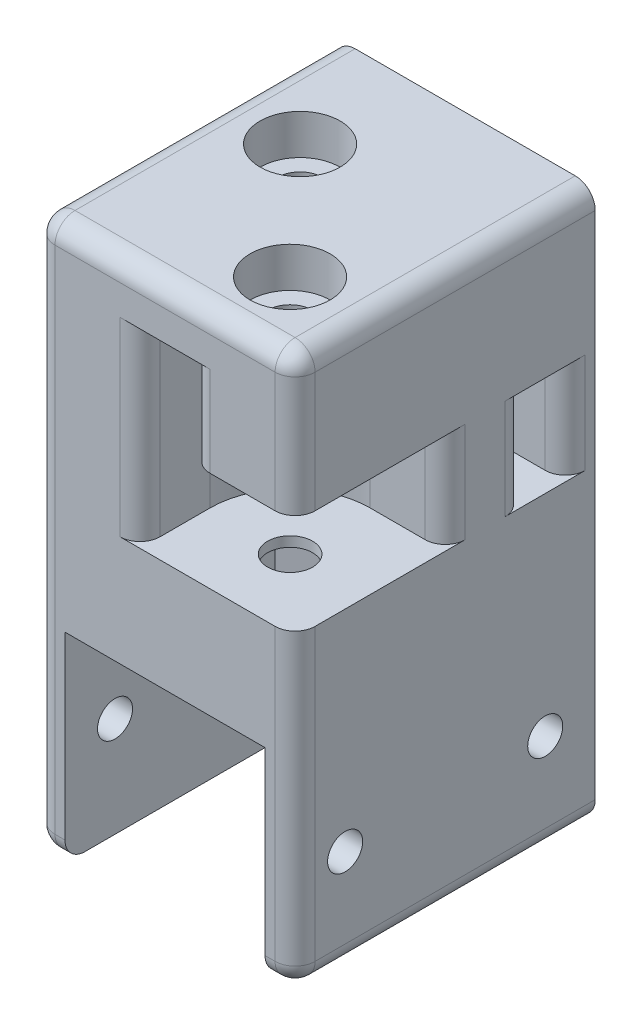
SolidWorks part; units mm, degrees
material "ABS"
ref_plane "Front Plane" through (0, 0, 0) normal (0, 0, 1) x (1, 0, 0)
ref_plane "Top Plane" through (0, 0, 0) normal (0, 1, 0) x (1, 0, 0)
ref_plane "Right Plane" through (0, 0, 0) normal (1, 0, 0) x (0, 0, -1)
sketch "Sketch2" plane through (0, 0, 0) normal (0, 1, 0) x (1, 0, 0)
  line L1 (-10, -15) -> (10, -15)
  line L2 (-10, -15) -> (-10, 15)
  line L3 (-10, 15) -> (10, 15)
  line L4 (10, -15) -> (10, 15)
  line L5 (-10, -15) -> (10, 15) construction
  line L6 (-10, 15) -> (10, -15) construction
  point P0 (0, 0)
  dimension "D1" = 20
  dimension "D2" = 30
extrude "Boss-Extrude1" add sketch "Sketch2" along normal blind 30
sketch "Sketch3" plane through (0, 30, 0) normal (0, 1, 0) x (1, 0, 0)
  line L0 (0, -15) -> (0, 15) construction
  line L1 (-10, -15) -> (10, -15) construction
  line L2 (10, 15) -> (-10, 15) construction
  line L3 (5.5, -1) -> (10, -1)
  line L4 (10, -15) -> (10, 15) construction
  line L6 (-5.5, 11) -> (-10, 11)
  line L7 (-10, 15) -> (-10, -15) construction
  line L8 (-10, 11) -> (-10, -1.3619)
  line L9 (-1.5, -8) -> (-1.5, -1.7446)
  line L10 (1.5, 4) -> (1.5, -2.2554)
  line L11 (-1.5, -8) -> (-1.5, -15)
  line L12 (1.5, -15) -> (1.5, -13.7446)
  line L13 (10, 11) -> (-5.5, 11)
  line L14 (10, 11) -> (10, 8)
  line L15 (10, 8) -> (0.2446, 8)
  line L17 (10, -15) -> (10, -1)
  line L18 (1.5, -15) -> (10, -15)
  line L19 (-5.5, -3) -> (-10, -3)
  line L20 (-10, -3) -> (-10, -1.3619)
  circle A0 centre (5.5, -8) radius 2.25
  circle A1 centre (-5.5, 4) radius 2.25
  arc A2 (5.5, -1) -> (1.5, -13.7446) centre (5.5, -8) ccw
  arc A3 (-5.5, 11) -> (-10, -1.3619) centre (-5.5, 4) cw
  line M1 (10, -15) -> (10, 15)
  line M3 (-10, 15) -> (-10, -15)
  line M4 (-10, -15) -> (10, -15)
  dimension "D3" = 4.5
  dimension "D4" = 4.5
  dimension "D7" = 7
  dimension "D8" = 7
  dimension "D1" = 5.5
  dimension "D2" = 7
  dimension "D5" = 12
  dimension "D6" = 5.5
  dimension "D9" = 3
extrude "Cut-Extrude2" cut sketch "Sketch3" against normal blind 19 contours L0 A2 L3 A0 M1 | A2 L0 | A3 L0 L6 A1 M3 | L0 A3 | L0 A2 L10 A3 | A2 L0 A3 L9 | L0 A2 L11 M4 | L0 L12 A2 M4 | L0 L15 L13 M1 | L15 L0 L13 A3 | L19 A3 M3
sketch "Sketch5" plane through (0, 30, 0) normal (0, 1, 0) x (1, 0, 0)
  line L1 (10, -15) -> (-10, -15)
  line L2 (10, -15) -> (10, 15)
  line L3 (10, 15) -> (-10, 15)
  line L4 (-10, -15) -> (-10, 15)
  line L5 (10, -15) -> (-10, 15) construction
  line L6 (10, 15) -> (-10, -15) construction
  point P0 (0, 0)
extrude "Boss-Extrude2" add sketch "Sketch5" along normal blind 5
sketch "Sketch6" plane through (0, 30, 0) normal (0, -1, 0) x (1, 0, 0)
  line L3 (-1.5, 15) -> (10, 15) construction
  line L8 (1.5, 2.2554) -> (1.5, 15)
  line L9 (-1.5, 15) -> (10, 15) construction
  line L10 (1.5, 15) -> (10, 15)
  line L11 (10, 15) -> (10, 1)
  line L12 (10, 1) -> (5.5, 1)
  line L13 (5.5, 1) -> (10, 1) construction
  circle A0 centre (5.5, 8) radius 2.2812
  arc A1 (5.5, 1) -> (1.5, 2.2554) centre (5.5, 8) cw
extrude "Boss-Extrude3" add sketch "Sketch6" along normal blind 9
sketch "Sketch7" plane through (0, 11, 0) normal (0, 1, 0) x (1, 0, 0)
  line L0 (0.2446, 8) -> (-10, 8)
  line L1 (-5.5, -3) -> (-10, -3)
  line L2 (-10, 11) -> (-10, -3) construction
  line L3 (-1.5, -15) -> (-1.5, -1.7446) construction
  line L4 (-1.5, -1.7446) -> (-1.5, -8)
  line L5 (1.5, -2.2554) -> (1.5, 4)
  line L6 (1.5, 4) -> (1.5, -2.2554) construction
  line L7 (-10, 8) -> (-10, -3)
  arc A0 (0.2446, 8) -> (1.5, 4) centre (-5.5, 4) cw
  arc A1 (-1.5, -1.7446) -> (-5.5, -3) centre (-5.5, 4) cw
  arc A2 (-5.5, -3) -> (-1.5, -1.7446) centre (-5.5, 4) ccw construction
  arc A3 (1.5, -2.2554) -> (-1.5, -8) centre (5.5, -8) ccw
  circle A4 centre (-5.5, 4) radius 2.25
  arc A5 (-5.5, -3) -> (-1.5, -1.7446) centre (-5.5, 4) ccw construction
extrude "Boss-Extrude4" add sketch "Sketch7" along normal blind 9
sketch "Sketch15" plane through (0, 30, 0) normal (0, -1, 0) x (1, 0, 0)
  line L0 (10, -11) -> (-10, -11) construction
  line L5 (10, -8) -> (10, -11)
  line L6 (10, -11) -> (-5.5, -11)
  line L7 (0.2446, -8) -> (10, -8)
  arc A0 (0.2446, -8) -> (-5.5, -11) centre (-5.5, -4) cw
extrude "Boss-Extrude6" add sketch "Sketch15" along normal blind 9
sketch "Sketch16" [suppressed] plane through (0, 11, 0) normal (0, 1, 0) x (1, 0, 0)
  line L0 (10, -15) -> (10, -1)
  line L1 (10, -1) -> (5.5, -1)
  line L2 (10, -15) -> (1.5, -15)
  line L3 (-1.5, -15) -> (10, -15) construction
  line L4 (1.5, -15) -> (1.5, -2.2554)
  circle A0 centre (5.5, -8) radius 2.25
  arc A1 (5.5, -1) -> (1.5, -2.2554) centre (5.5, -8) ccw construction
  arc A2 (1.5, -2.2554) -> (5.5, -1) centre (5.5, -8) cw
  dimension "D1" = 3
extrude "Boss-Extrude7" [suppressed] add sketch "Sketch16" along normal blind 9
sketch "Sketch17" [suppressed] plane through (0, 30, 0) normal (0, -1, 0) x (1, 0, 0)
  line L0 (0.2446, -8) -> (-10, -8)
  line L1 (-10, -11) -> (-10, 3) construction
  line L2 (-10, -8) -> (-10, 3)
  line L3 (1.5, -4) -> (1.5, 15) construction
  line L4 (1.5, -4) -> (1.5, 2.2554)
  line L5 (-1.5, 8.0934) -> (-1.5, 1.7446)
  line L6 (-1.5, 15) -> (-1.5, 1.7446) construction
  line L7 (-5.5, 3) -> (-10, 3)
  line L8 (-5.5, 3) -> (-10, 3) construction
  circle A0 centre (-5.5, -4) radius 2.25
  arc A1 (-1.5, 1.7446) -> (-5.5, 3) centre (-5.5, -4) ccw
  arc A2 (-1.5, 1.7446) -> (-5.5, 3) centre (-5.5, -4) ccw construction
  arc A3 (0.2446, -8) -> (1.5, -4) centre (-5.5, -4) ccw
  arc A4 (1.5, 2.2554) -> (-1.5, 8) centre (5.5, 8) cw
  arc A5 (-1.5, 1.7446) -> (-5.5, 3) centre (-5.5, -4) ccw construction
  circle M1 centre (-5.5, -4) radius 2.25
  line M2 (-10, 3) -> (-10, -11)
  arc M6 (-5.5, -11) -> (1.5, -4) centre (-5.5, -4) ccw
  line M7 (1.5, -4) -> (1.5, 15)
  arc M13 (-1.5, 1.7446) -> (-5.5, 3) centre (-5.5, -4) ccw
extrude "Boss-Extrude8" [suppressed] add sketch "Sketch17" along normal blind 9 contours A4 L5 L0 M7 M13 M2 M6 M1
sketch "Sketch18" [suppressed] plane through (0, 11, 0) normal (0, 1, 0) x (1, 0, 0)
  line L0 (10, 11) -> (10, 8)
  line L1 (10, 8) -> (0.2446, 8)
  line L2 (10, 11) -> (-10, 11) construction
  line L3 (10, 11) -> (-5.5, 11)
  arc A0 (0.2446, 8) -> (-5.5, 11) centre (-5.5, 4) ccw
extrude "Boss-Extrude9" [suppressed] add sketch "Sketch18" along normal blind 9
sketch "Sketch9" [suppressed] plane through (0, 0, -15) normal (0, 0, -1) x (-1, 0, 0)
  line L0 (-10, 0) -> (10, 0) construction
  line L1 (-5.5, 3) -> (5.5, 3)
  line L2 (-5.5, 3) -> (-5.5, 0)
  line L3 (-5.5, 0) -> (5.5, 0)
  line L4 (5.5, 3) -> (5.5, 0)
  line L5 (-5.5, 3) -> (5.5, 0) construction
  line L6 (-5.5, 0) -> (5.5, 3) construction
  line L9 (-10, 35) -> (-10, 0) construction
  point P0 (0, 1.5)
  dimension "D1" = 3
  dimension "D2" = 11
  dimension "D3" = 4.5
extrude "Boss-Extrude5" [suppressed] add sketch "Sketch9" along normal blind 7
sketch "Sketch10" [suppressed] plane through (0, 3, 0) normal (0, 1, 0) x (1, 0, 0)
  line L0 (-5.5, 15) -> (5.5, 15) construction
  circle A0 centre (0, 18.5) radius 1.75
  dimension "D1" = 3.5
  dimension "D2" = 3.5
extrude "Cut-Extrude4" [suppressed] cut sketch "Sketch10" against normal through all
sketch "Sketch11" [suppressed] plane through (0, 3, 0) normal (0, 1, 0) x (1, 0, 0)
  circle A0 centre (0, 18.5) radius 3
  dimension "D1" = 6
extrude "Cut-Extrude5" [suppressed] cut sketch "Sketch11" against normal blind 1
sketch "Sketch8" plane through (0, 35, 0) normal (0, 1, 0) x (1, 0, 0)
  line L0 (0, -15) -> (0, 15) construction
  line L1 (-10, -15) -> (10, -15) construction
  line L2 (10, 15) -> (-10, 15) construction
  circle A0 centre (5.5, -8) radius 2.25
  circle A1 centre (-5.5, 4) radius 2.25
  dimension "D1" = 4.5
  dimension "D2" = 4.5
  dimension "D3" = 7
  dimension "D4" = 5.5
  dimension "D5" = 5.5
  dimension "D6" = 12
extrude "Cut-Extrude3" cut sketch "Sketch8" against normal through all
hole_wizard "CBORE for M4 Hex Socket Head Cap Screw1" positions "Sketch12" profile "Sketch13" counterbore size "M4" standard "ISO" end condition up to next
sketch "Sketch12" plane through (0, 35, 0) normal (0, 1, 0) x (1, 0, 0)
  point P0 (5.5, -8)
  point P3 (-5.5, 4)
sketch "Sketch13" plane through (5.5, 35, 8) normal (1, 0, 0) x (0, 0, 1)
  line L0 (0, 0) -> (0, 35)
  line L1 (0, 35) -> (2.25, 35)
  line L3 (2.25, 35) -> (2.25, 4)
  line L4 (2.25, 4) -> (4, 4)
  line L5 (4, 4) -> (4, 0)
  line L7 (4, 0) -> (0, 0)
  line L11 (0, -6.35) -> (0, 107.95) construction
  dimension "Thru Hole Dia." = 4.5
  dimension "Thru Hole Depth" = 35
  dimension "C'Bore Dia." = 8
  dimension "C'Bore Depth" = 4
sketch "Sketch14" plane through (0, 0, 0) normal (0, -1, 0) x (1, 0, 0)
  line L1 (5.5, 3.8142) -> (9.125, 5.9071)
  line L2 (9.125, 5.9071) -> (9.125, 10.0929)
  line L3 (9.125, 10.0929) -> (5.5, 12.1858)
  line L4 (5.5, 12.1858) -> (1.875, 10.0929)
  line L5 (1.875, 10.0929) -> (1.875, 5.9071)
  line L6 (1.875, 5.9071) -> (5.5, 3.8142)
  line L7 (-5.5, -8.1858) -> (-1.875, -6.0929)
  line L8 (-1.875, -6.0929) -> (-1.875, -1.9071)
  line L9 (-1.875, -1.9071) -> (-5.5, 0.1858)
  line L10 (-5.5, 0.1858) -> (-9.125, -1.9071)
  line L11 (-9.125, -1.9071) -> (-9.125, -6.0929)
  line L12 (-9.125, -6.0929) -> (-5.5, -8.1858)
  circle A0 centre (5.5, 8) radius 3.625 construction
  circle A1 centre (-5.5, -4) radius 3.625 construction
  dimension "D1" = 7.25
  dimension "D2" = 7.25
extrude "Cut-Extrude6" cut sketch "Sketch14" against normal blind 10
sketch "Sketch21" [suppressed] plane through (0, 20, 0) normal (0, 1, 0) x (1, 0, 0)
  line L3 (10, 0) -> (5.5, 0)
  line L4 (10, -15) -> (-2.5, -15)
  line L5 (-2.5, -15) -> (-2.5, -8)
  line L6 (10, -15) -> (10, 0)
  arc A0 (5.5, 0) -> (-2.5, -8) centre (5.5, -8) ccw
  dimension "D1" = 8
extrude "Cut-Extrude8" [suppressed] cut sketch "Sketch21" along normal blind 10
sketch "Sketch23" plane through (0, 11, 0) normal (0, 1, 0) x (1, 0, 0)
  line L36 (-11, 12) -> (-11, -4)
  line L37 (-11, -4) -> (-5.5, -4)
  line L38 (-2.5, -3.4162) -> (-2.5, -16)
  line L39 (-2.5, -16) -> (2.5, -16)
  line L40 (2.5, -16) -> (2.5, 4)
  line L41 (-5.5, 12) -> (-11, 12)
  line L42 (-11, 12) -> (-11, -4)
  line L43 (-11, -4) -> (-5.5, -4)
  line L44 (-2.5, -3.4162) -> (-2.5, -16)
  line L45 (-2.5, -16) -> (2.5, -16)
  line L46 (2.5, -16) -> (2.5, 4)
  line L47 (-5.5, 12) -> (-11, 12)
  arc A12 (-5.5, -4) -> (-2.5, -3.4162) centre (-5.5, 4) ccw
  arc A13 (2.5, 4) -> (-5.5, 12) centre (-5.5, 4) ccw
  arc A14 (-5.5, -4) -> (-2.5, -3.4162) centre (-5.5, 4) ccw
  arc A15 (2.5, 4) -> (-5.5, 12) centre (-5.5, 4) ccw
  dimension "D1" = 1
extrude "Cut-Extrude9" [suppressed] cut sketch "Sketch23" along normal blind 10
sketch "Sketch27" [suppressed] plane through (-10, 0, 0) normal (-1, 0, 0) x (0, 0, 1)
  line L0 (-12, 21) -> (-12, 11) construction
  line L1 (-8, 30) -> (-12, 30)
  line L2 (-8, 30) -> (-8, 20)
  line L3 (-8, 20) -> (-12, 20)
  line L4 (-12, 30) -> (-12, 20)
  dimension "D1" = 10
extrude "Cut-Extrude13" [suppressed] cut sketch "Sketch27" against normal through all
sketch "Sketch24" plane through (0, 11, 0) normal (0, 1, 0) x (1, 0, 0)
  line L16 (-2.5, -16) -> (11, -16)
  line L17 (11, -16) -> (11, 0)
  line L18 (11, 0) -> (5.5, 0)
  line L19 (-2.5, -8) -> (-2.5, -16)
  line L20 (-2.5, -16) -> (11, -16)
  line L21 (11, -16) -> (11, 0)
  line L22 (11, 0) -> (5.5, 0)
  line L23 (-2.5, -8) -> (-2.5, -16)
  arc A6 (5.5, 0) -> (-2.5, -8) centre (5.5, -8) ccw
  arc A7 (5.5, 0) -> (-2.5, -8) centre (5.5, -8) ccw
  dimension "D1" = 1
extrude "Cut-Extrude10" cut sketch "Sketch24" along normal blind 10
sketch "Sketch25" plane through (0, 30, 0) normal (0, -1, 0) x (1, 0, 0)
  line L4 (-10, -12) -> (-10, 4)
  line L5 (2.5, -4) -> (2.5, 15)
  line L6 (-10, -12) -> (-5.5, -12)
  line L7 (2.5, -4) -> (2.5, 15)
  line L8 (-10, -12) -> (-5.5, -12)
  line L9 (-5.5, 4) -> (-10, 4)
  line L10 (-5.5, 4) -> (-10, 4)
  line L13 (2.5, 15) -> (-2.5, 15)
  line L15 (-2.5, 15) -> (-2.5, 3.4162)
  arc A4 (-5.5, -12) -> (2.5, -4) centre (-5.5, -4) ccw
  arc A5 (-5.5, -12) -> (2.5, -4) centre (-5.5, -4) ccw
  arc A7 (-5.5, 4) -> (-2.5, 3.4162) centre (-5.5, -4) cw
  arc A8 (-0.9286, 2.5652) -> (-5.5, 4) centre (-5.5, -4) ccw
  dimension "D3" = 5
  dimension "D1" = 1
  dimension "D2" = 1
extrude "Cut-Extrude11" cut sketch "Sketch25" along normal blind 10
sketch "Sketch26" plane through (-10, 0, 0) normal (-1, 0, 0) x (0, 0, 1)
  line L0 (-12, 20) -> (-12, 30) construction
  line L1 (-8, 11) -> (-12, 11)
  line L2 (-8, 11) -> (-8, 21)
  line L3 (-8, 21) -> (-12, 21)
  line L4 (-12, 11) -> (-12, 21)
  dimension "D1" = 10
extrude "Cut-Extrude12" cut sketch "Sketch26" against normal through all
sketch "Sketch28" [suppressed] plane through (-10, 0, 0) normal (-1, 0, 0) x (0, 0, 1)
  line L0 (-15, 35) -> (15, 35) construction
  line L2 (-15, 35) -> (-15, 0) construction
  line L3 (-15, 35) -> (15, 35)
  line L4 (15, 35) -> (15, 0)
  line L5 (-15, 35) -> (-15, 0)
  line L6 (-12, 30) -> (-12, 11)
  line L7 (4, 30) -> (-12, 30)
  line L10 (4, 11) -> (4, 30)
  line L11 (-12, 11) -> (4, 11)
  line L12 (-12, 30) -> (-12, 11)
  line L13 (4, 30) -> (-12, 30)
  line L16 (4, 11) -> (4, 30)
  line L17 (-12, 11) -> (4, 11)
  line L18 (-15, 0) -> (15, 0)
  line L19 (-15, 0) -> (15, 0) construction
  dimension "D1" = 0
extrude "Boss-Extrude11" [suppressed] add sketch "Sketch28" along normal blind 3
sketch "Sketch30" [suppressed] plane through (10, 0, 0) normal (1, 0, 0) x (0, 0, -1)
  line L0 (-15, 35) -> (15, 35) construction
  line L1 (8, 30) -> (12, 30) construction
  line L2 (12, 30) -> (12, 20) construction
  line L3 (8, 20) -> (12, 20) construction
  line L4 (8, 20) -> (8, 30) construction
  line L5 (15, 35) -> (15, 0) construction
  line L6 (-15, 20) -> (0, 20) construction
  line L7 (0, 30) -> (0, 20) construction
  line L8 (-15, 30) -> (0, 30) construction
  line L9 (-15, 35) -> (-15, 30) construction
  line L10 (-15, 35) -> (15, 35)
  line L11 (8, 30) -> (12, 30)
  line L12 (12, 30) -> (12, 20)
  line L13 (8, 20) -> (12, 20)
  line L14 (8, 20) -> (8, 30)
  line L15 (15, 35) -> (15, 0)
  line L16 (-15, 20) -> (0, 20)
  line L17 (0, 30) -> (0, 20)
  line L18 (-15, 30) -> (0, 30)
  line L19 (-15, 35) -> (-15, 30)
  line L20 (-15, 20) -> (-15, 0)
  line L21 (-15, 0) -> (15, 0) construction
  line L22 (-15, 0) -> (15, 0)
extrude "Boss-Extrude13" [suppressed] add sketch "Sketch30" along normal blind 3
sketch "Sketch32" plane through (-10, 0, 0) normal (-1, 0, 0) x (0, 0, 1)
  line L0 (-15, 35) -> (15, 35) construction
  line L1 (-15, 35) -> (-15, 0) construction
  line L2 (-12, 11) -> (-8, 11) construction
  line L3 (-8, 20) -> (-8, 11) construction
  line L4 (-12, 11) -> (-12, 30) construction
  line L5 (-12, 30) -> (4, 30) construction
  line L6 (4, 20) -> (4, 30) construction
  line L7 (-8, 20) -> (4, 20) construction
  line L8 (-15, 35) -> (15, 35)
  line L9 (-15, 35) -> (-15, 0)
  line L10 (-12, 11) -> (-8, 11)
  line L11 (-8, 20) -> (-8, 11)
  line L12 (-12, 11) -> (-12, 30)
  line L13 (-12, 30) -> (4, 30)
  line L14 (4, 20) -> (4, 30)
  line L15 (-8, 20) -> (4, 20)
  line L16 (15, 35) -> (15, 0)
  line L17 (-15, 0) -> (15, 0) construction
  line L18 (15, 0) -> (-15, 0)
extrude "Boss-Extrude15" add sketch "Sketch32" along normal blind 3
sketch "Sketch33" plane through (10, 0, 0) normal (1, 0, 0) x (0, 0, -1)
  line L0 (8, 11) -> (12, 11) construction
  line L1 (8, 11) -> (8, 21) construction
  line L2 (12, 21) -> (12, 11) construction
  line L3 (12, 21) -> (8, 21) construction
  line L4 (15, 35) -> (15, 0) construction
  line L5 (-15, 35) -> (15, 35) construction
  line L6 (-15, 11) -> (0, 11) construction
  line L7 (0, 11) -> (0, 21) construction
  line L8 (0, 21) -> (-15, 21) construction
  line L9 (-15, 35) -> (-15, 21) construction
  line L10 (8, 11) -> (12, 11)
  line L11 (8, 11) -> (8, 21)
  line L12 (12, 21) -> (12, 11)
  line L13 (12, 21) -> (8, 21)
  line L14 (15, 35) -> (15, 0)
  line L15 (-15, 35) -> (15, 35)
  line L16 (-15, 11) -> (0, 11)
  line L17 (0, 11) -> (0, 21)
  line L18 (0, 21) -> (-15, 21)
  line L19 (-15, 35) -> (-15, 21)
  line L20 (-15, 11) -> (-15, 0)
  line L21 (-15, 0) -> (15, 0) construction
  line L22 (-15, 0) -> (15, 0)
extrude "Boss-Extrude16" add sketch "Sketch33" along normal blind 3
sketch "Sketch29" [suppressed] plane through (0, 0, 0) normal (0, -1, 0) x (1, 0, 0)
  line L0 (13, -15) -> (-13, -15) construction
  line L1 (-13, 15) -> (-10, 15)
  line L2 (-13, 15) -> (-13, -15)
  line L3 (-13, -15) -> (-10, -15)
  line L4 (-10, 15) -> (-10, -15)
  dimension "D1" = 3
extrude "Boss-Extrude12" [suppressed] add sketch "Sketch29" along normal blind 20
sketch "Sketch31" [suppressed] plane through (0, 0, 0) normal (0, -1, 0) x (1, 0, 0)
  line L0 (13, -15) -> (5.5, -15) construction
  line L1 (13, 15) -> (10, 15)
  line L2 (13, 15) -> (13, -15)
  line L3 (13, -15) -> (10, -15)
  line L4 (10, 15) -> (10, -15)
  dimension "D1" = 3
extrude "Boss-Extrude14" [suppressed] add sketch "Sketch31" along normal blind 20
sketch "Sketch34" plane through (0, 0, 0) normal (0, -1, 0) x (1, 0, 0)
  line L0 (13, -15) -> (-13, -15) construction
  line L1 (-13, 15) -> (-10, 15)
  line L2 (-13, 15) -> (-13, -15)
  line L3 (-13, -15) -> (-10, -15)
  line L4 (-10, 15) -> (-10, -15)
extrude "Boss-Extrude17" add sketch "Sketch34" along normal blind 20
sketch "Sketch35" plane through (0, 0, 0) normal (0, -1, 0) x (1, 0, 0)
  line L0 (13, -15) -> (-10, -15) construction
  line L1 (13, 15) -> (10, 15)
  line L2 (13, 15) -> (13, -15)
  line L3 (13, -15) -> (10, -15)
  line L4 (10, 15) -> (10, -15)
  dimension "D1" = 3
extrude "Boss-Extrude18" add sketch "Sketch35" along normal blind 20
sketch "Sketch36" [suppressed] plane through (-13, 0, 0) normal (-1, 0, 0) x (0, 0, 1)
  line L0 (-15, 0) -> (15, 0) construction
  line L1 (15, -20) -> (15, 35) construction
  line L2 (-15, 35) -> (-15, -20) construction
  circle A0 centre (-10, -10) radius 1.3011
  circle A1 centre (10, -10) radius 1.4145
  dimension "D1" = 10
  dimension "D2" = 10
  dimension "D3" = 5
  dimension "D4" = 5
extrude "Cut-Extrude14" [suppressed] cut sketch "Sketch36" against normal through all
sketch "Sketch37" plane through (-13, 0, 0) normal (-1, 0, 0) x (0, 0, 1)
  line L0 (-15, 0) -> (15, 0) construction
  line L1 (-15, 35) -> (-15, -20) construction
  line L2 (15, -20) -> (15, 35) construction
  circle A0 centre (-10, -10) radius 1.75
  circle A1 centre (10, -10) radius 1.75
  dimension "D3" = 3.5
  dimension "D5" = 3.5
  dimension "D1" = 10
  dimension "D2" = 5
  dimension "D4" = 5
extrude "Cut-Extrude15" cut sketch "Sketch37" against normal through all
mirror "Mirror1" [suppressed]
delete or keep bodies "Body-Delete/Keep 1" [suppressed] type keep bodies bodies 116
fillet "Fillet1-r" radius 2 10 edges at (-13, 7.5, 15) (-13, 35, 0) (13, 35, 0) (13, 28, 15) (13, -4.5, 15) (-13, -20, 0) (-11.5, -20, 15) (13, -20, 0) (11.5, -20, 15) (0, 35, 15)
fillet "Fillet2-r" radius 2 9 edges at (-2.5, 25, 3.4162) (2.5, 25.5, 15) (-2.5, 20.5, 15) (13, 16, -12) (13, 16, 0) (13, 16, -8) (-13, 25, 4) (-13, 15.5, -8) (-13, 20.5, -12)
fillet "Fillet3-r" [suppressed] radius 2
fillet "Fillet4-l" [suppressed] radius 2
fillet "Fillet5-l" [suppressed] radius 2
